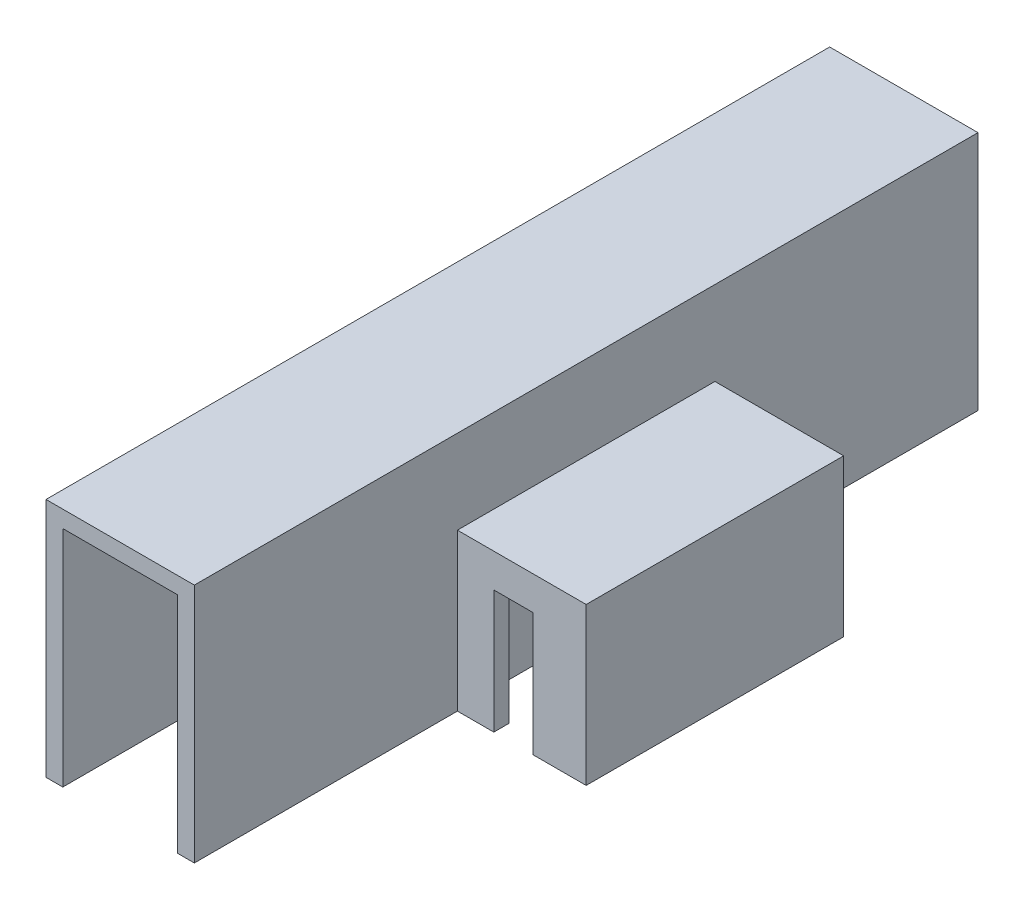
SolidWorks part; units mm, degrees
ref_plane "Front Plane" through (0, 0, 0) normal (0, 0, 1) x (1, 0, 0)
ref_plane "Top Plane" through (0, 0, 0) normal (0, 1, 0) x (1, 0, 0)
ref_plane "Right Plane" through (0, 0, 0) normal (1, 0, 0) x (0, 0, -1)
sketch "Sketch1" plane through (0, 0, 0) normal (0, 1, 0) x (1, 0, 0)
  line L1 (-13, 23) -> (13, 23)
  line L2 (-13, 23) -> (-13, -23)
  line L3 (-13, -23) -> (13, -23)
  line L4 (13, 23) -> (13, -23)
  line L5 (-13, 23) -> (13, -23) construction
  line L6 (-13, -23) -> (13, 23) construction
  line L7 (-10.25, 20.25) -> (10.25, 20.25)
  line L8 (-10.25, 20.25) -> (-10.25, -20.25)
  line L9 (-10.25, -20.25) -> (10.25, -20.25)
  line L10 (10.25, 20.25) -> (10.25, -20.25)
  line L11 (-10.25, 20.25) -> (10.25, -20.25) construction
  line L12 (-10.25, -20.25) -> (10.25, 20.25) construction
  point P0 (0, 0)
  point P2 (0, 0)
extrude "Boss-Extrude1" add sketch "Sketch1" along normal blind 26
sketch "Sketch2" plane through (0, 26, 0) normal (0, 1, 0) x (1, 0, 0)
  line L1 (-13, 23) -> (13, 23)
  line L2 (-13, 23) -> (-13, -23)
  line L3 (-13, -23) -> (13, -23)
  line L4 (13, 23) -> (13, -23)
  line L5 (-13, 23) -> (13, -23) construction
  line L6 (-13, -23) -> (13, 23) construction
  point P0 (0, 0)
extrude "Boss-Extrude2" add sketch "Sketch2" along normal blind 2
sketch "Sketch3" plane through (0, 0, 0) normal (0, -1, 0) x (1, 0, 0)
  line L0 (-10.25, 20.25) -> (10.25, 20.25) construction
  line L1 (-3.5, 23) -> (3.5, 23)
  line L9 (-3.5, 23) -> (-3.5, 20)
  line L10 (-3.5, 20) -> (3.5, 20)
  line L11 (3.5, 23) -> (3.5, 20)
  point P0 (0, 20.25)
extrude "Cut-Extrude1" cut sketch "Sketch3" against normal blind 22
sketch "Sketch6" plane through (0, 0, 23) normal (0, 0, 1) x (1, 0, 0)
  line L6 (-13, 0) -> (-10, 0)
  line L7 (-13, 0) -> (-13, 40)
  line L8 (-13, 40) -> (-10, 40)
  line L9 (-10, 0) -> (-10, 40)
extrude "Boss-Extrude5" add sketch "Sketch6" along normal blind 7
sketch "Sketch7" plane through (0, 0, -23) normal (0, 0, -1) x (-1, 0, 0)
  line L6 (13, 0) -> (10, 0)
  line L7 (13, 0) -> (13, 40)
  line L8 (13, 40) -> (10, 40)
  line L9 (10, 0) -> (10, 40)
extrude "Boss-Extrude6" add sketch "Sketch7" along normal blind 7
sketch "Sketch8" plane through (-10, 0, 0) normal (1, 0, 0) x (0, 0, -1)
  line L1 (-23, 40) -> (23, 40)
  line L2 (-23, 40) -> (-23, 28)
  line L3 (-23, 28) -> (23, 28)
  line L4 (23, 40) -> (23, 28)
extrude "Boss-Extrude7" add sketch "Sketch8" against normal blind 3
sketch "Sketch10" plane through (0, 40, 0) normal (0, 1, 0) x (1, 0, 0)
  line L1 (-10, 30) -> (-33.5, 30)
  line L2 (-10, 30) -> (-10, -30)
  line L3 (-10, -30) -> (-33.5, -30)
  line L4 (-33.5, 30) -> (-33.5, -30)
extrude "Boss-Extrude8" add sketch "Sketch10" along normal blind 3
sketch "Sketch11" plane through (-33.5, 0, 0) normal (-1, 0, 0) x (0, 0, 1)
  line L1 (-30, 43) -> (30, 43)
  line L2 (-30, 43) -> (-30, 0)
  line L3 (-30, 0) -> (30, 0)
  line L4 (30, 43) -> (30, 0)
extrude "Boss-Extrude9" add sketch "Sketch11" along normal blind 3
sketch "Sketch12" plane through (0, 0, 30) normal (0, 0, 1) x (1, 0, 0)
  line L0 (-33.5, 0) -> (-36.5, 0)
  line L1 (-36.5, 0) -> (-36.5, 43)
  line L2 (-36.5, 0) -> (-36.5, 43) construction
  line L3 (-36.5, 43) -> (-10, 43)
  line L4 (-10, 0) -> (-10, 43) construction
  line L5 (-36.5, 43) -> (-10, 43) construction
  line L6 (-10, 43) -> (-10, 0)
  line L7 (-10, 0) -> (-13, 0)
  line L8 (-13, 0) -> (-13, 40)
  line L9 (-13, 40) -> (-33.5, 40)
  line L10 (-33.5, 40) -> (-33.5, 0)
extrude "Boss-Extrude10" add sketch "Sketch12" along normal blind 40
sketch "Sketch13" plane through (0, 0, -30) normal (0, 0, -1) x (-1, 0, 0)
  line L0 (13, 0) -> (10, 0)
  line L1 (10, 0) -> (10, 43)
  line L2 (10, 43) -> (10, 0) construction
  line L3 (10, 43) -> (36.5, 43)
  line L4 (36.5, 43) -> (36.5, 0)
  line L5 (36.5, 0) -> (33.5, 0)
  line L6 (33.5, 0) -> (33.5, 40)
  line L7 (33.5, 40) -> (13, 40)
  line L8 (13, 40) -> (13, 0)
extrude "Boss-Extrude11" add sketch "Sketch13" along normal blind 40
